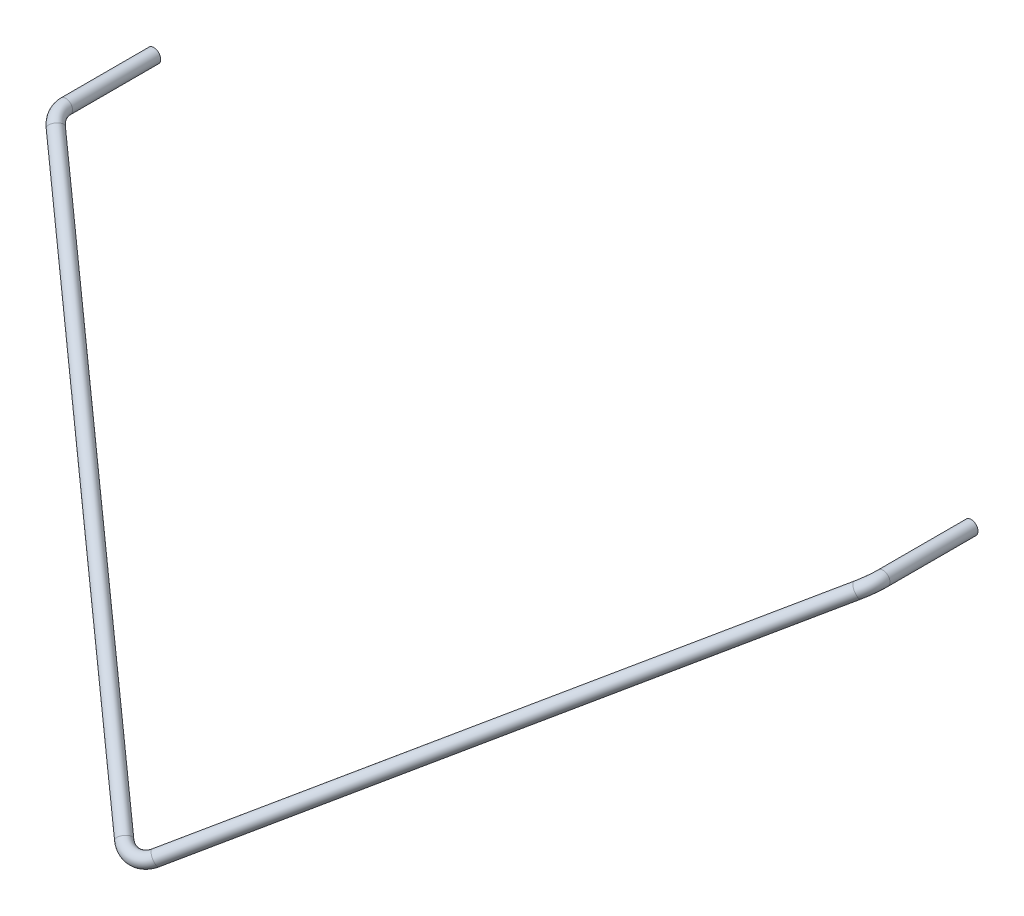
SolidWorks part; units mm, degrees
material "Acero al carbono no aleado"
ref_plane "Alzado" through (0, 0, 0) normal (0, 0, 1) x (1, 0, 0)
ref_plane "Planta" through (0, 0, 0) normal (0, 1, 0) x (1, 0, 0)
ref_plane "Vista lateral" through (0, 0, 0) normal (1, 0, 0) x (0, 0, -1)
ref_plane "Plano1" through (1520, 0, 0) normal (1, 0, 0) x (0, 0, -1)
sketch "Croquis2" plane through (0, 0, 0) normal (1, 0, 0) x (0, 0, -1)
  point P0 (-1250, -1050)
  dimension "D1" = 1050
  dimension "D2" = 1250
ref_plane "Plano2" through (-1520, 0, 0) normal (1, 0, 0) x (0, 0, -1)
sketch "Croquis3" plane through (1520, 0, 0) normal (1, 0, 0) x (0, 0, -1)
  line L0 (0, 0) -> (370, 0) construction
  line L1 (971.1223, 0) -> (-971.1223, 0) construction
  point P0 (0, 0)
  dimension "D1" = 370
sketch "Croquis4" plane through (-1520, 0, 0) normal (1, 0, 0) x (0, 0, -1)
  line L0 (0, 0) -> (370, 0) construction
  line L1 (0, 0) -> (370, 0) construction
sketch3d "Croquis3D1"
  line L0 (-1520, 0, -370) -> (-1520, 0, -42.4622)
  line L1 (-1491.0644, -19.9884, 23.7957) -> (-58.5497, -1009.5545, 1201.8506)
  line L2 (58.5497, -1009.5545, 1201.8506) -> (1491.0644, -19.9884, 23.7957)
  line L3 (1520, 0, -42.4622) -> (1520, 0, -370)
  arc A0 (-58.5497, -1009.5545, 1201.8506) -> (58.5497, -1009.5545, 1201.8506) centre (0, -974.4906, 1160.1078) ccw
  arc A1 (1491.0644, -19.9884, 23.7957) -> (1520, 0, -42.4622) centre (1454.1779, -45.4692, -42.4622) ccw
  arc A2 (-1520, 0, -42.4622) -> (-1491.0644, -19.9884, 23.7957) centre (-1454.1779, -45.4692, -42.4622) ccw
  point P12 (0, -1050, 1250)
  point P13 (0, -913.2342, 1211.5632)
  point P16 (1520, 0, 0)
  point P17 (1408.7087, 20.3529, -42.4622)
  point P20 (-1520, 0, 0)
  point P21 (-1408.7087, 20.3529, -42.4622)
  dimension "D1" = 80
  dimension "D2" = 80
ref_plane "Plano3" through (0, 0, -370) normal (0, 0, 1) x (1, 0, 0)
sketch "Croquis5" plane through (0, 0, -370) normal (0, 0, 1) x (1, 0, 0)
  circle A0 centre (-1520, 0) radius 25.4
  dimension "D1" = 50.8
sweep "Barrer1" add profiles "Croquis5" path "Croquis3D1"
